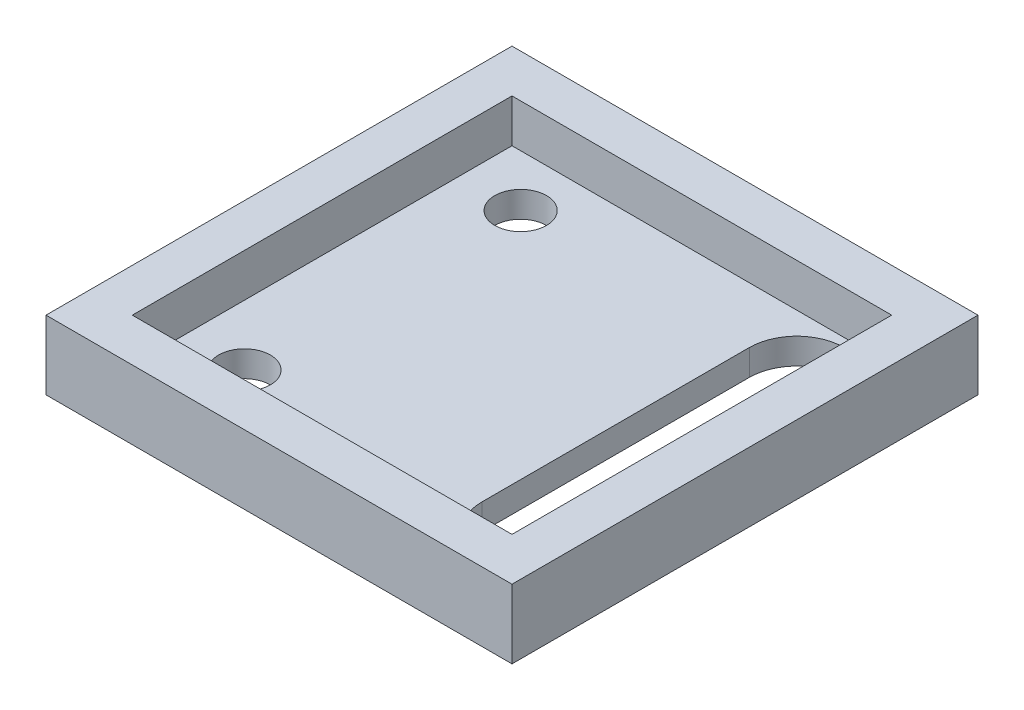
SolidWorks part; units mm, degrees
ref_plane "Front Plane" through (0, 0, 0) normal (0, 0, 1) x (1, 0, 0)
ref_plane "Top Plane" through (0, 0, 0) normal (0, 1, 0) x (1, 0, 0)
ref_plane "Right Plane" through (0, 0, 0) normal (1, 0, 0) x (0, 0, -1)
sketch "Sketch2" plane through (0, 0, 0) normal (0, 1, 0) x (1, 0, 0)
  line L1 (0, 0) -> (27, 0)
  line L2 (0, 0) -> (0, 27)
  line L3 (0, 27) -> (27, 27)
  line L4 (27, 0) -> (27, 27)
  dimension "D1" = 27
  dimension "D2" = 27
extrude "Boss-Extrude1" add sketch "Sketch2" along normal blind 4 contours L2 L1 L4 L3
sketch "Sketch5" plane through (0, 4, 0) normal (0, 1, 0) x (1, 0, 0)
  line L0 (0, 0) -> (27, 0) construction
  line L1 (27, 0) -> (27, 27) construction
  line L5 (2.5, 24.5) -> (24.5, 24.5)
  line L6 (2.5, 24.5) -> (2.5, 2.5)
  line L7 (2.5, 2.5) -> (24.5, 2.5)
  line L8 (24.5, 24.5) -> (24.5, 2.5)
  line L9 (2.5, 24.5) -> (24.5, 2.5) construction
  line L10 (2.5, 2.5) -> (24.5, 24.5) construction
  point P0 (13.5, 13.5)
  dimension "D1" = 22
  dimension "D2" = 22
  dimension "D3" = 2.5
  dimension "D4" = 2.5
extrude "Cut-Extrude2" cut sketch "Sketch5" against normal blind 2.5
sketch "Sketch3" plane through (0, 0, 0) normal (0, -1, 0) x (-1, 0, 0)
  line L3 (0, 27) -> (-27, 27) construction
  circle A1 centre (-6, 21.5) radius 1.5
  circle A2 centre (-6, 5.5) radius 1.5
  dimension "D1" = 3
  dimension "D2" = 3
  dimension "D5" = 16
  dimension "D7" = 6
  dimension "D8" = 5.5
extrude "Cut-Extrude3" cut sketch "Sketch3" against normal blind 10
sketch "Sketch6" plane through (0, 1.5, 0) normal (0, 1, 0) x (1, 0, 0)
  line L0 (0, 27) -> (27, 27) construction
  line L2 (19.5, 21.25) -> (19.5, 5.75)
  line L4 (24.5, 2.5) -> (24.5, 24.5)
  line L5 (24.5, 24.5) -> (2.5, 24.5)
  line L6 (2.5, 24.5) -> (2.5, 2.5)
  line L7 (2.5, 2.5) -> (24.5, 2.5)
  line L8 (24.5, 5.75) -> (24.5, 21.25)
  line L12 (24.5, 21.25) -> (24.5, 5.75)
  line L13 (0, 0) -> (27, 0) construction
  arc A0 (22.25, 3) -> (24.5, 5.75) centre (21.6944, 5.75) ccw
  arc A1 (24.5, 21.25) -> (22.25, 24) centre (21.6944, 21.25) ccw
  arc A2 (19.5, 5.75) -> (22.25, 3) centre (22.25, 5.75) ccw
  arc A3 (22.25, 24) -> (19.5, 21.25) centre (22.25, 21.25) ccw
  line M7 (24.5, 2.5) -> (24.5, 24.5)
  dimension "D2" = 0
  dimension "D3" = 3
  dimension "D4" = 3
  dimension "D1" = 0
extrude "Cut-Extrude4" cut sketch "Sketch6" against normal blind 10 contours A1 A3 L2 A2 A0 M7
